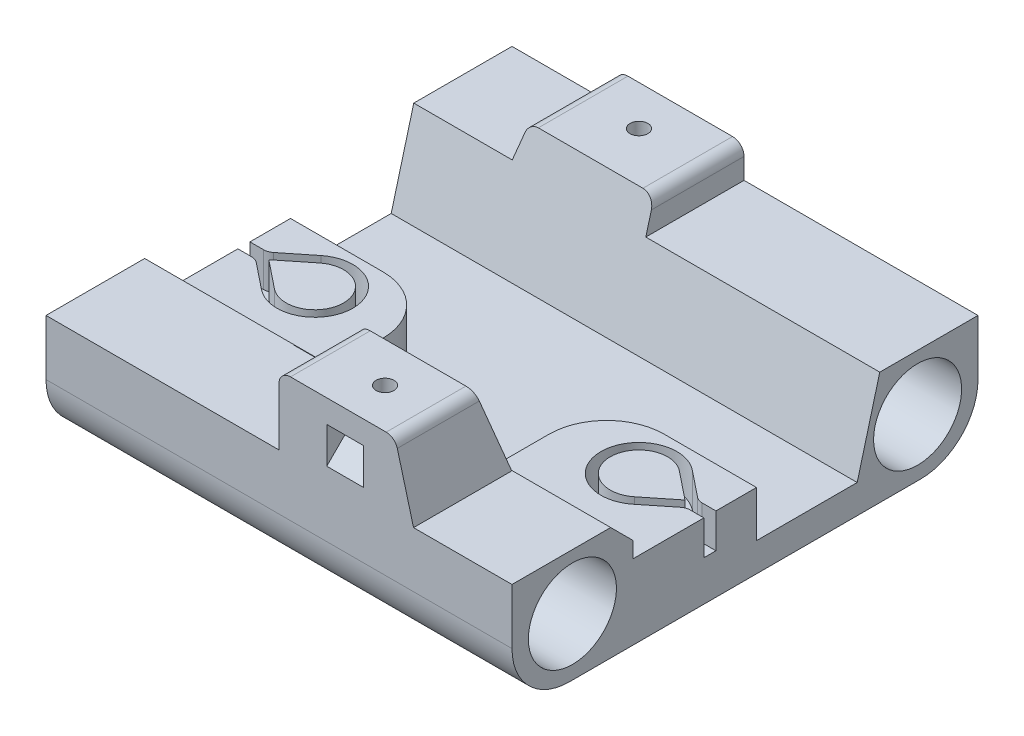
SolidWorks part; units mm, degrees
material "PLA (20%–30% infill + wall)"
ref_plane "Front Plane" through (0, 0, 0) normal (0, 0, 1) x (1, 0, 0)
ref_plane "Top Plane" through (0, 0, 0) normal (0, 1, 0) x (1, 0, 0)
ref_plane "Right Plane" through (0, 0, 0) normal (1, 0, 0) x (0, 0, -1)
sketch "Sketch1" plane through (0, 0, 0) normal (0, 1, 0) x (1, 0, 0)
  line L1 (-40.5, 40.5) -> (40.5, 40.5)
  line L2 (-40.5, 40.5) -> (-40.5, -40.5)
  line L3 (-40.5, -40.5) -> (40.5, -40.5)
  line L4 (40.5, 40.5) -> (40.5, -40.5)
  line L5 (-40.5, 40.5) -> (40.5, -40.5) construction
  line L6 (-40.5, -40.5) -> (40.5, 40.5) construction
  point P0 (0, 0)
  dimension "D1" = 81
  dimension "D2" = 81
extrude "Boss-Extrude1" add sketch "Sketch1" along normal blind 5
sketch "Sketch2" plane through (-40.5, 0, 0) normal (-1, 0, 0) x (0, 0, 1)
  line L0 (-30, 10) -> (-30, 5) construction
  line L1 (19.5, 5) -> (23.4255, 19.65)
  line L2 (-40.5, 5) -> (40.5, 5) construction
  line L3 (0, 0) -> (0, 23.7181) construction
  line L4 (-40.5, 5) -> (-40.5, 19.65)
  line L5 (-40.5, 19.65) -> (40.5, 19.65)
  line L6 (40.5, 5) -> (40.5, 19.65)
  line L7 (-40.5, 5) -> (40.5, 5)
  line L8 (-19.5, 5) -> (-23.4255, 19.65)
  circle A0 centre (-30, 10) radius 7.65
  circle A1 centre (-30, 10) radius 4 construction
  circle A2 centre (30, 10) radius 7.65
  circle A3 centre (30, 10) radius 4 construction
  point P14 (-30, 17.65)
  point P18 (0, 19.65)
  line M6 (40.5, 5) -> (-40.5, 5)
  dimension "D1" = 15.3
  dimension "D2" = 8
  dimension "D3" = 5
  dimension "D4" = 60
  dimension "D5" = 2
  dimension "D6" = 90
  dimension "D7" = 75
  dimension "D8" = 10.5
extrude "Boss-Extrude3" add sketch "Sketch2" against normal up to surface (81 mm away) contours A0 L7 L8 L5 L4 | A2 L6 L5 L1 M6 up to face at (40.5, 2.5, 0)
sketch "Sketch4" plane through (-40.5, 0, 0) normal (-1, 0, 0) x (0, 0, 1)
  circle A0 centre (-30, 10) radius 7.65
  circle A1 centre (30, 10) radius 7.65
  arc A2 (35.7899, 5) -> (24.2101, 5) centre (30, 10) ccw construction
  arc A3 (-24.2101, 5) -> (-35.7899, 5) centre (-30, 10) ccw construction
extrude "Cut-Extrude2" cut sketch "Sketch4" against normal through all
sketch "Sketch6" plane through (0, 5, 0) normal (0, 1, 0) x (1, 0, 0)
  line L0 (-40.5, 0) -> (40.5, 0) construction
  line L1 (-40.5, 19.5) -> (-40.5, -19.5) construction
  line L2 (40.5, -19.5) -> (40.5, 19.5) construction
  line L3 (-32.2909, -0.9479) -> (-37.4144, -5.05)
  line L4 (-31.2909, -2.1969) -> (-36.1659, -6.1)
  line L5 (-36.1659, -6.1) -> (-31.2909, -10.0031)
  line L6 (-40.5, 0) -> (40.5, 0)
  line L9 (40.5, 0) -> (40.5, -2.4666)
  line L10 (-37.4144, -7.15) -> (-32.2909, -11.2521)
  line L11 (-40.5, -5.05) -> (-37.4144, -5.05)
  line L12 (-28.1659, -6.1) -> (-47.8801, -6.1) construction
  line L13 (-40.5, -7.15) -> (-37.4144, -7.15)
  line L14 (-32.2909, -0.9479) -> (-38.7259, -6.1) construction
  line L15 (-38.7259, -6.1) -> (-32.2909, -11.2521) construction
  line L16 (-40.5, -5.05) -> (-40.5, 2)
  line L17 (-40.5, 2) -> (-14.4463, 2)
  line L18 (-14.4463, 2) -> (-14.4463, -19.5)
  line L19 (40.5, -19.5) -> (-40.5, -19.5) construction
  line L20 (-14.4463, -19.5) -> (-40.5, -19.5)
  line L21 (-40.5, -19.5) -> (-40.5, -7.15)
  arc A0 (-31.2909, -10.0031) -> (-31.2909, -2.1969) centre (-28.1659, -6.1) ccw
  arc A1 (-32.2909, -11.2521) -> (-32.2909, -0.9479) centre (-28.1659, -6.1) ccw
  circle A2 centre (-28.1659, -6.1) radius 5 construction
  circle A3 centre (-28.1659, -6.1) radius 6.6 construction
  line M6 (-40.5, 19.5) -> (-40.5, -19.5)
  line M7 (-40.5, -19.5) -> (40.5, -19.5)
  dimension "D1" = 10
  dimension "D2" = 6.1
  dimension "D3" = 8
  dimension "D4" = 1.6
  dimension "D5" = 1.05
  dimension "D6" = 2
extrude "Boss-Extrude4" add sketch "Sketch6" along normal blind 10 contours A1 L10 L13 L18 L6 L11 L3 M6 M7 | L5 A0 L4 | L18 L17 L6 M6
sketch "Sketch7" plane through (-40.5, 0, 0) normal (-1, 0, 0) x (0, 0, 1)
  line L0 (19.5, 5) -> (19.5, 19.65)
  line L1 (19.5, 19.65) -> (23.4255, 19.65)
  line L2 (23.4255, 19.65) -> (19.5, 5)
extrude "Boss-Extrude6" add sketch "Sketch7" against normal up to surface (26.0537 mm away) up to face at (-14.4463, 10, 8.75)
chamfer "Chamfer1" distance 3.85 angle 45 1 edges at (-27.4732, 19.65, 19.5)
ref_plane "Plane1" through (0, 0, 0) normal (-1, 0, 0) x (0, 0, 1)
mirror "Mirror1" about plane through (0, 0, 0) normal (-1, 0, 0) of "Boss-Extrude4", "Boss-Extrude6", "Chamfer1"
fillet "Fillet2" radius 2 4 edges at (-37.4144, 10, 7.15) (-37.4144, 10, 5.05) (37.4144, 10, 5.05) (37.4144, 10, 7.15)
fillet "Fillet3" radius 10 2 edges at (0, 0, -40.5) (0, 0, 40.5)
sketch "Sketch8" plane through (0, 0, 0) normal (-1, 0, 0) x (0, 0, 1)
  circle A0 centre (30, 10) radius 6
  circle A1 centre (-30, 10) radius 6
  circle A2 centre (30, 10) radius 7.65 construction
  circle A3 centre (-30, 10) radius 7.65 construction
  circle A4 centre (30, 10) radius 7.65
  circle A5 centre (-30, 10) radius 7.65
  dimension "D1" = 12
  dimension "D2" = 12
extrude "Boss-Extrude7" add sketch "Sketch8" along normal mid plane 33
sketch "Sketch9" plane through (0, 0, 40.5) normal (0, 0, 1) x (1, 0, 0)
  line L0 (0, 10) -> (0, 29.3) construction
  line L1 (-40.5, 10) -> (40.5, 10) construction
  line L2 (0, 10.7938) -> (0, -10.7938) construction
  line L3 (-23.385, 19.65) -> (23.385, 19.65)
  line L5 (40.5, 19.65) -> (-40.5, 19.65) construction
  line L6 (-23.385, 19.65) -> (-19.495, 34.15)
  line L7 (-19.495, 34.15) -> (19.495, 34.15)
  line L8 (19.495, 34.15) -> (23.385, 19.65)
  line L9 (-20.1657, 31.65) -> (20.1657, 31.65)
  point P12 (0, 19.65)
  dimension "D1" = 46.77
  dimension "D2" = 3.89
  dimension "D3" = 14.5
  dimension "D4" = 12
extrude "Boss-Extrude8" add sketch "Sketch9" against normal up to surface (13.8592 mm away)
ref_plane "Plane2" through (0, 0, 0) normal (0, 0, 1) x (1, 0, 0)
sketch "Sketch10" plane through (0, 0, -40.5) normal (0, 0, -1) x (-1, 0, 0)
  line L1 (23.385, 19.65) -> (20.1657, 31.65)
  line L2 (-23.385, 19.65) -> (-20.1657, 31.65) construction
  line L5 (-23.385, 19.65) -> (-20.1657, 31.65)
  line L6 (-23.385, 19.65) -> (23.385, 19.65)
  line L9 (20.1657, 31.65) -> (-20.1657, 31.65)
extrude "Boss-Extrude9" add sketch "Sketch10" against normal up to surface (13.8592 mm away)
sketch "Sketch11" plane through (0, 31.65, 0) normal (0, 1, 0) x (1, 0, 0)
  line L0 (-20.1657, -33.5704) -> (20.1657, -33.5704) construction
  line L1 (-20.1657, -26.6408) -> (-20.1657, -40.5) construction
  line L2 (20.1657, -26.6408) -> (20.1657, -40.5) construction
  line L3 (0, 10.7938) -> (0, -10.7938) construction
  line L4 (-11.8937, 0) -> (11.8937, 0) construction
  circle A0 centre (-11.5, -33.5704) radius 1.55
  circle A1 centre (11.5, -33.5704) radius 1.55
  circle A2 centre (11.5, 33.5704) radius 1.55
  circle A3 centre (-11.5, 33.5704) radius 1.55
  dimension "D1" = 3.1
  dimension "D2" = 23
extrude "Cut-Extrude3" cut sketch "Sketch11" against normal blind 15 contours A3 | L0 A1 | A1 L0
sketch "Sketch12" plane through (0, 15, 0) normal (0, 1, 0) x (1, 0, 0)
  line L0 (31.2909, -10.0031) -> (36.1659, -6.1) construction
  line L1 (36.1659, -6.1) -> (31.2909, -2.1969) construction
  line L2 (-36.1659, -6.1) -> (-31.2909, -10.0031) construction
  line L3 (-31.2909, -2.1969) -> (-36.1659, -6.1) construction
  line L4 (31.2909, -10.0031) -> (36.1659, -6.1)
  line L5 (36.1659, -6.1) -> (31.2909, -2.1969)
  line L6 (-36.1659, -6.1) -> (-31.2909, -10.0031)
  line L7 (-31.2909, -2.1969) -> (-36.1659, -6.1)
  line L9 (32.2909, -0.9479) -> (36.8664, -4.6112)
  line L10 (38.1164, -5.05) -> (40.5, -5.05)
  line L11 (40.5, -5.05) -> (40.5, 2)
  line L12 (40.5, 2) -> (14.4463, 2)
  line L13 (14.4463, 2) -> (14.4463, -19.5)
  line L14 (14.4463, -19.5) -> (40.5, -19.5)
  line L15 (40.5, -19.5) -> (40.5, -7.15)
  line L16 (40.5, -7.15) -> (38.1164, -7.15)
  line L17 (36.8664, -7.5888) -> (32.2909, -11.2521)
  line L18 (32.2909, -0.9479) -> (36.8664, -4.6112)
  line L19 (38.1164, -5.05) -> (40.5, -5.05)
  line L20 (40.5, -5.05) -> (40.5, 2)
  line L21 (40.5, 2) -> (14.4463, 2)
  line L22 (14.4463, 2) -> (14.4463, -19.5)
  line L23 (14.4463, -19.5) -> (40.5, -19.5)
  line L24 (40.5, -19.5) -> (40.5, -7.15)
  line L25 (40.5, -7.15) -> (38.1164, -7.15)
  line L26 (36.8664, -7.5888) -> (32.2909, -11.2521)
  line L27 (-32.2909, -11.2521) -> (-36.8664, -7.5888)
  line L28 (-38.1164, -7.15) -> (-40.5, -7.15)
  line L29 (-40.5, -7.15) -> (-40.5, -19.5)
  line L30 (-40.5, -19.5) -> (-14.4463, -19.5)
  line L31 (-14.4463, -19.5) -> (-14.4463, 2)
  line L32 (-14.4463, 2) -> (-40.5, 2)
  line L33 (-40.5, 2) -> (-40.5, -5.05)
  line L34 (-40.5, -5.05) -> (-38.1164, -5.05)
  line L35 (-36.8664, -4.6112) -> (-32.2909, -0.9479)
  line L36 (-32.2909, -11.2521) -> (-36.8664, -7.5888)
  line L37 (-38.1164, -7.15) -> (-40.5, -7.15)
  line L38 (-40.5, -7.15) -> (-40.5, -19.5)
  line L39 (-40.5, -19.5) -> (-14.4463, -19.5)
  line L40 (-14.4463, -19.5) -> (-14.4463, 2)
  line L41 (-14.4463, 2) -> (-40.5, 2)
  line L42 (-40.5, 2) -> (-40.5, -5.05)
  line L43 (-40.5, -5.05) -> (-38.1164, -5.05)
  line L44 (-36.8664, -4.6112) -> (-32.2909, -0.9479)
  arc A0 (31.2909, -2.1969) -> (31.2909, -10.0031) centre (28.1659, -6.1) ccw construction
  arc A1 (-31.2909, -10.0031) -> (-31.2909, -2.1969) centre (-28.1659, -6.1) ccw construction
  arc A2 (31.2909, -2.1969) -> (31.2909, -10.0031) centre (28.1659, -6.1) ccw
  arc A3 (36.8664, -4.6112) -> (38.1164, -5.05) centre (38.1164, -3.05) ccw
  arc A4 (38.1164, -7.15) -> (36.8664, -7.5888) centre (38.1164, -9.15) ccw
  arc A5 (32.2909, -0.9479) -> (32.2909, -11.2521) centre (28.1659, -6.1) ccw
  arc A6 (36.8664, -4.6112) -> (38.1164, -5.05) centre (38.1164, -3.05) ccw
  arc A7 (38.1164, -7.15) -> (36.8664, -7.5888) centre (38.1164, -9.15) ccw
  arc A8 (32.2909, -0.9479) -> (32.2909, -11.2521) centre (28.1659, -6.1) ccw
  arc A9 (-36.8664, -7.5888) -> (-38.1164, -7.15) centre (-38.1164, -9.15) ccw
  arc A10 (-38.1164, -5.05) -> (-36.8664, -4.6112) centre (-38.1164, -3.05) ccw
  arc A11 (-32.2909, -11.2521) -> (-32.2909, -0.9479) centre (-28.1659, -6.1) ccw
  arc A12 (-36.8664, -7.5888) -> (-38.1164, -7.15) centre (-38.1164, -9.15) ccw
  arc A13 (-38.1164, -5.05) -> (-36.8664, -4.6112) centre (-38.1164, -3.05) ccw
  arc A14 (-32.2909, -11.2521) -> (-32.2909, -0.9479) centre (-28.1659, -6.1) ccw
  arc A15 (-31.2909, -10.0031) -> (-31.2909, -2.1969) centre (-28.1659, -6.1) ccw
  dimension "D1" = 0
  dimension "D2" = 0
extrude "Cut-Extrude4" cut sketch "Sketch12" against normal blind 2
sketch "Sketch13" plane through (0, 5, 0) normal (0, 1, 0) x (1, 0, 0)
  line L5 (32.2909, -11.2521) -> (36.8664, -7.5888)
  line L6 (38.1164, -7.15) -> (40.5, -7.15)
  line L7 (40.5, -7.15) -> (40.5, -5.05)
  line L8 (40.5, -5.05) -> (38.1164, -5.05)
  line L9 (36.8664, -4.6112) -> (32.2909, -0.9479)
  line L10 (32.2909, -11.2521) -> (36.8664, -7.5888)
  line L11 (38.1164, -7.15) -> (40.5, -7.15)
  line L12 (40.5, -7.15) -> (40.5, -5.05)
  line L13 (40.5, -5.05) -> (38.1164, -5.05)
  line L14 (36.8664, -4.6112) -> (32.2909, -0.9479)
  line L15 (-40.5, -7.15) -> (-38.1164, -7.15)
  line L16 (-36.8664, -7.5888) -> (-32.2909, -11.2521)
  line L17 (-32.2909, -0.9479) -> (-36.8664, -4.6112)
  line L18 (-38.1164, -5.05) -> (-40.5, -5.05)
  line L19 (-40.5, -5.05) -> (-40.5, -7.15)
  line L20 (-40.5, -7.15) -> (-38.1164, -7.15)
  line L21 (-36.8664, -7.5888) -> (-32.2909, -11.2521)
  line L22 (-32.2909, -0.9479) -> (-36.8664, -4.6112)
  line L23 (-38.1164, -5.05) -> (-40.5, -5.05)
  line L24 (-40.5, -5.05) -> (-40.5, -7.15)
  arc A3 (38.1164, -7.15) -> (36.8664, -7.5888) centre (38.1164, -9.15) ccw
  arc A4 (36.8664, -4.6112) -> (38.1164, -5.05) centre (38.1164, -3.05) ccw
  arc A5 (32.2909, -0.9479) -> (32.2909, -11.2521) centre (28.1659, -6.1) ccw
  arc A6 (38.1164, -7.15) -> (36.8664, -7.5888) centre (38.1164, -9.15) ccw
  arc A7 (36.8664, -4.6112) -> (38.1164, -5.05) centre (38.1164, -3.05) ccw
  arc A8 (32.2909, -0.9479) -> (32.2909, -11.2521) centre (28.1659, -6.1) ccw
  arc A9 (-36.8664, -7.5888) -> (-38.1164, -7.15) centre (-38.1164, -9.15) ccw
  arc A10 (-32.2909, -11.2521) -> (-32.2909, -0.9479) centre (-28.1659, -6.1) ccw
  arc A11 (-38.1164, -5.05) -> (-36.8664, -4.6112) centre (-38.1164, -3.05) ccw
  arc A12 (-36.8664, -7.5888) -> (-38.1164, -7.15) centre (-38.1164, -9.15) ccw
  arc A13 (-32.2909, -11.2521) -> (-32.2909, -0.9479) centre (-28.1659, -6.1) ccw
  arc A14 (-38.1164, -5.05) -> (-36.8664, -4.6112) centre (-38.1164, -3.05) ccw
  dimension "D1" = 0
  dimension "D2" = 0
extrude "Boss-Extrude10" add sketch "Sketch13" along normal blind 2
fillet "Fillet4" radius 10 2 edges at (-14.4463, 9, -2) (14.4463, 9, -2)
sketch "Sketch15" plane through (0, 0, -40.5) normal (0, 0, -1) x (-1, 0, 0)
  line L0 (20.1657, 31.65) -> (-20.1657, 31.65) construction
  line L1 (20.1657, 31.65) -> (0.1657, 31.65)
  line L2 (0.1657, 31.65) -> (0.1657, 25.25)
  line L3 (0.1657, 25.25) -> (21.8827, 25.25)
  line L5 (21.8827, 25.25) -> (20.1657, 31.65)
  line L6 (23.385, 19.65) -> (20.1657, 31.65) construction
  dimension "D1" = 6.4
  dimension "D2" = 20
extrude "Cut-Extrude5" cut sketch "Sketch15" against normal up to surface (13.8592 mm away)
fillet "Fillet5" radius 2 1 edges at (-0.1657, 31.65, -33.5704)
fillet "Fillet6" radius 2 3 edges at (-20.1657, 31.65, 33.5704) (20.1657, 31.65, 33.5704) (20.1657, 31.65, -33.5704)
fillet "Fillet7" radius 2 1 edges at (-21.8827, 25.25, -32.713)
ref_plane "Plane3" through (0, 27.65, 0) normal (0, 1, 0) x (1, 0, 0)
sketch "Sketch16" plane through (0, 27.65, 0) normal (0, 1, 0) x (1, 0, 0)
  line L0 (-18.6315, -40.5) -> (18.6315, -40.5) construction
  line L1 (-14.7, -30.5671) -> (-8.3, -30.5671)
  line L2 (-14.7, -30.5671) -> (-14.7, -36.5671)
  line L4 (-8.3, -30.5671) -> (-8.3, -36.5671)
  line L5 (-14.7, -30.5671) -> (-8.3, -36.5671) construction
  line L6 (-14.7, -36.5671) -> (-8.3, -30.5671) construction
  line L8 (-14.7, -36.5671) -> (-14.7, -40.5)
  line L9 (-14.7, -40.5) -> (-8.3, -40.5)
  line L10 (-8.3, -36.5671) -> (-8.3, -40.5)
  line L11 (0, 10.8075) -> (0, -10.8075) construction
  line L12 (14.7, -36.5671) -> (14.7, -40.5)
  line L13 (14.7, -40.5) -> (8.3, -40.5)
  line L14 (8.3, -36.5671) -> (8.3, -40.5)
  line L15 (8.3, -30.5671) -> (8.3, -36.5671)
  line L16 (14.7, -30.5671) -> (8.3, -30.5671)
  line L17 (14.7, -30.5671) -> (14.7, -36.5671)
  line L18 (-11.9075, 0) -> (11.9075, 0) construction
  line L19 (14.7, 40.5) -> (8.3, 40.5)
  line L20 (14.7, 36.5671) -> (14.7, 40.5)
  line L21 (14.7, 30.5671) -> (14.7, 36.5671)
  line L22 (14.7, 30.5671) -> (8.3, 30.5671)
  line L23 (8.3, 30.5671) -> (8.3, 36.5671)
  line L24 (8.3, 36.5671) -> (8.3, 40.5)
  point P0 (-11.5, -33.5671)
  dimension "D1" = 6.4
  dimension "D2" = 6
extrude "Cut-Extrude6" cut sketch "Sketch16" against normal blind 2.5
chamfer "Chamfer2" distance 3.8 angle 45 3 edges at (11.5, 25.15, 40.5) (-11.5, 25.15, 40.5) (11.5, 25.15, -40.5)
sketch "Sketch17" plane through (0, 0, 40.5) normal (0, 0, 1) x (1, 0, 0)
  line L0 (-18.6315, 31.65) -> (18.6315, 31.65) construction
  line L1 (0, 31.65) -> (-23.385, 31.65)
  line L2 (0, 31.65) -> (0, 19.65)
  line L3 (0, 19.65) -> (-23.385, 19.65)
  line L4 (-23.385, 31.65) -> (-23.385, 19.65)
extrude "Cut-Extrude7" cut sketch "Sketch17" against normal up to surface (13.8592 mm away)
sketch "Sketch19" plane through (0, 0, -40.5) normal (0, 0, -1) x (-1, 0, 0)
  line L0 (0.1657, 29.65) -> (0.1657, 25.25) construction
  line L1 (-23.385, 19.65) -> (0.1657, 19.65)
  line L2 (-23.385, 19.65) -> (-23.385, 31.65)
  line L3 (-23.385, 31.65) -> (0.1657, 31.65)
  line L4 (0.1657, 19.65) -> (0.1657, 31.65)
  line L5 (-1.8343, 31.65) -> (-18.6315, 31.65) construction
extrude "Cut-Extrude8" cut sketch "Sketch19" against normal up to surface (17.0745 mm away)
fillet "Fillet8" radius 2 2 edges at (0, 31.65, 33.5704) (-0.1657, 25.25, -32.713)
